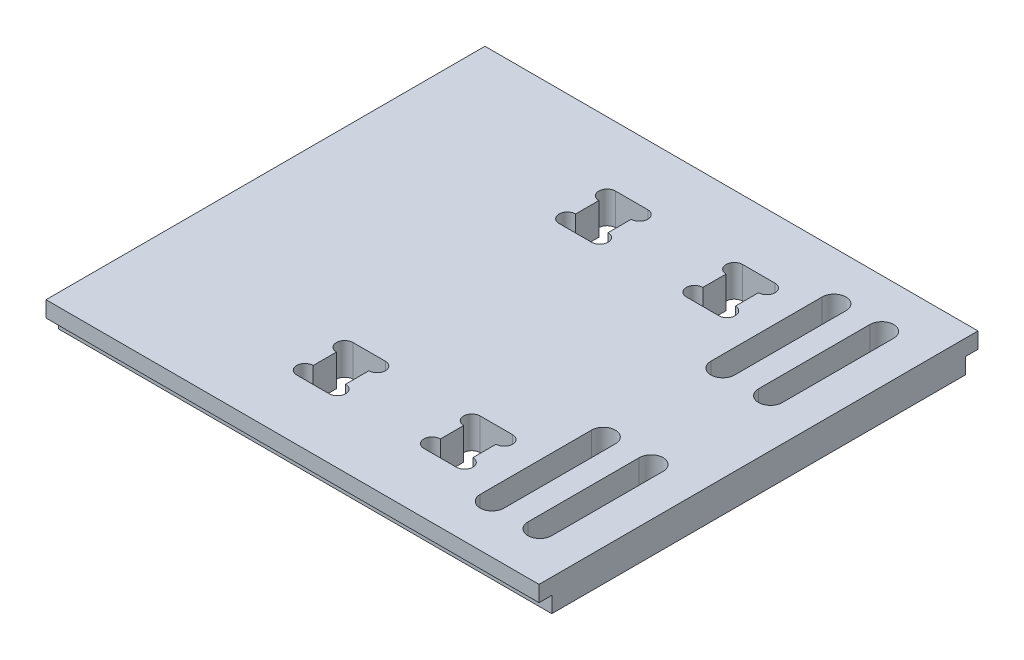
SolidWorks part; units mm, degrees
material "Delrin 2700 NC010, Low Viscosity Acetal Copolymer (SS)"
ref_plane "Front Plane" through (0, 0, 0) normal (0, 0, 1) x (1, 0, 0)
ref_plane "Top Plane" through (0, 0, 0) normal (0, 1, 0) x (1, 0, 0)
ref_plane "Right Plane" through (0, 0, 0) normal (1, 0, 0) x (0, 0, -1)
sketch "Sketch1" plane through (0, 0, 0) normal (1, 0, 0) x (0, 0, -1)
  line L1 (-87.63, -6.35) -> (87.63, -6.35)
  line L2 (-87.63, -6.35) -> (-87.63, 6.35)
  line L3 (-87.63, 6.35) -> (87.63, 6.35)
  line L4 (87.63, -6.35) -> (87.63, 6.35)
  line L5 (-87.63, -6.35) -> (87.63, 6.35) construction
  line L6 (-87.63, 6.35) -> (87.63, -6.35) construction
  point P0 (0, 0)
  dimension "D1" = 175.26
  dimension "D2" = 12.7
extrude "Boss-Extrude1" add sketch "Sketch1" along normal mid plane 196.85
sketch "Sketch2" plane through (98.425, 0, 0) normal (1, 0, 0) x (0, 0, -1)
  line L0 (87.63, 6.35) -> (-87.63, 6.35) construction
  line L1 (-87.63, -6.35) -> (-82.55, -6.35)
  line L2 (-87.63, -6.35) -> (-87.63, 0)
  line L3 (-87.63, 0) -> (-82.55, 0)
  line L4 (-82.55, -6.35) -> (-82.55, 0)
  line L5 (87.63, -6.35) -> (82.55, -6.35)
  line L6 (87.63, -6.35) -> (87.63, 0)
  line L7 (87.63, 0) -> (82.55, 0)
  line L8 (82.55, -6.35) -> (82.55, 0)
  dimension "D1" = 6.35
  dimension "D2" = 165.1
extrude "Cut-Extrude1" cut sketch "Sketch2" against normal through all
sketch "Sketch3" plane through (0, 6.35, 0) normal (0, 1, 0) x (1, 0, 0)
  line L0 (98.425, 87.63) -> (98.425, -87.63) construction
  line L1 (28.448, -41.148) -> (41.402, -41.148)
  line L2 (28.448, -47.752) -> (28.448, -57.023)
  line L3 (28.448, -63.627) -> (41.402, -63.627)
  line L4 (41.402, -47.752) -> (41.402, -57.023)
  line L5 (-22.352, -41.148) -> (-9.398, -41.148)
  line L6 (-9.398, -47.752) -> (-9.398, -57.023)
  line L7 (-22.352, -63.627) -> (-9.398, -63.627)
  line L8 (-22.352, -47.752) -> (-22.352, -57.023)
  line L9 (-22.352, 63.627) -> (-9.398, 63.627)
  line L10 (-9.398, 57.023) -> (-9.398, 47.752)
  line L11 (-22.352, 41.148) -> (-9.398, 41.148)
  line L12 (-22.352, 57.023) -> (-22.352, 47.752)
  line L13 (28.448, 63.627) -> (41.402, 63.627)
  line L14 (41.402, 57.023) -> (41.402, 47.752)
  line L15 (28.448, 41.148) -> (41.402, 41.148)
  line L16 (28.448, 57.023) -> (28.448, 47.752)
  line L17 (28.448, -41.148) -> (-22.352, -41.148) construction
  line L18 (28.448, -41.148) -> (28.448, 63.627) construction
  arc A0 (28.448, -41.148) -> (28.448, -47.752) centre (28.448, -44.45) ccw
  arc A1 (28.448, -57.023) -> (28.448, -63.627) centre (28.448, -60.325) ccw
  arc A2 (41.402, -63.627) -> (41.402, -57.023) centre (41.402, -60.325) ccw
  arc A3 (41.402, -47.752) -> (41.402, -41.148) centre (41.402, -44.45) ccw
  arc A4 (-9.398, -47.752) -> (-9.398, -41.148) centre (-9.398, -44.45) ccw
  arc A5 (-9.398, -63.627) -> (-9.398, -57.023) centre (-9.398, -60.325) ccw
  arc A6 (-22.352, -57.023) -> (-22.352, -63.627) centre (-22.352, -60.325) ccw
  arc A7 (-22.352, -41.148) -> (-22.352, -47.752) centre (-22.352, -44.45) ccw
  arc A8 (-9.398, 57.023) -> (-9.398, 63.627) centre (-9.398, 60.325) ccw
  arc A9 (-9.398, 41.148) -> (-9.398, 47.752) centre (-9.398, 44.45) ccw
  arc A10 (-22.352, 47.752) -> (-22.352, 41.148) centre (-22.352, 44.45) ccw
  arc A11 (-22.352, 63.627) -> (-22.352, 57.023) centre (-22.352, 60.325) ccw
  arc A12 (41.402, 57.023) -> (41.402, 63.627) centre (41.402, 60.325) ccw
  arc A13 (41.402, 41.148) -> (41.402, 47.752) centre (41.402, 44.45) ccw
  arc A14 (28.448, 47.752) -> (28.448, 41.148) centre (28.448, 44.45) ccw
  arc A15 (28.448, 63.627) -> (28.448, 57.023) centre (28.448, 60.325) ccw
  point P11 (34.925, -41.148)
  point P18 (41.402, -52.3875)
  point P19 (98.425, 0)
  dimension "D3" = 6.604
  dimension "D1" = 12.954
  dimension "D2" = 22.479
  dimension "D4" = 63.5
  dimension "D5" = 52.3875
  dimension "D8" = 50.8
  dimension "D9" = 104.775
  dimension "D6" = 2
  dimension "D7" = 2
extrude "Cut-Extrude2" cut sketch "Sketch3" against normal through all
sketch "Sketch4" plane through (0, 6.35, 0) normal (0, 1, 0) x (1, 0, 0)
  line L0 (60.325, -68.2625) -> (60.325, -23.8125) construction
  line L1 (55.5625, -68.2625) -> (55.5625, -23.8125)
  line L2 (65.0875, -68.2625) -> (65.0875, -23.8125)
  line L3 (60.325, 23.8125) -> (60.325, 68.2625) construction
  line L4 (55.5625, 23.8125) -> (55.5625, 68.2625)
  line L5 (65.0875, 23.8125) -> (65.0875, 68.2625)
  line L6 (79.375, 68.2625) -> (79.375, 23.8125) construction
  line L7 (84.1375, 68.2625) -> (84.1375, 23.8125)
  line L8 (74.6125, 68.2625) -> (74.6125, 23.8125)
  line L9 (79.375, -23.8125) -> (79.375, -68.2625) construction
  line L10 (84.1375, -23.8125) -> (84.1375, -68.2625)
  line L11 (74.6125, -23.8125) -> (74.6125, -68.2625)
  line L12 (98.425, 87.63) -> (98.425, -87.63) construction
  arc A0 (55.5625, -68.2625) -> (65.0875, -68.2625) centre (60.325, -68.2625) ccw
  arc A1 (65.0875, -23.8125) -> (55.5625, -23.8125) centre (60.325, -23.8125) ccw
  arc A2 (55.5625, 23.8125) -> (65.0875, 23.8125) centre (60.325, 23.8125) ccw
  arc A3 (65.0875, 68.2625) -> (55.5625, 68.2625) centre (60.325, 68.2625) ccw
  arc A4 (84.1375, 68.2625) -> (74.6125, 68.2625) centre (79.375, 68.2625) ccw
  arc A5 (74.6125, 23.8125) -> (84.1375, 23.8125) centre (79.375, 23.8125) ccw
  arc A6 (84.1375, -23.8125) -> (74.6125, -23.8125) centre (79.375, -23.8125) ccw
  arc A7 (74.6125, -68.2625) -> (84.1375, -68.2625) centre (79.375, -68.2625) ccw
  point P2 (60.325, -46.0375)
  point P7 (60.325, 46.0375)
  point P14 (79.375, 46.0375)
  point P21 (79.375, -46.0375)
  point P28 (63.1729, -55.4474)
  point P29 (0, 0)
  point P30 (0, 0)
  point P33 (98.425, 0)
  dimension "D1" = 4.7625
  dimension "D2" = 44.45
  dimension "D3" = 92.075
  dimension "D4" = 46.0375
  dimension "D5" = 38.1
  dimension "D6" = 19.05
extrude "Cut-Extrude3" cut sketch "Sketch4" against normal through all
equation "\"D1@Boss-Extrude1\"=7.66629343in "
equation "\"D5@Sketch3\"=4.125/2"
equation "\"D4@Sketch4\"=\"D3@Sketch4\"/2"
